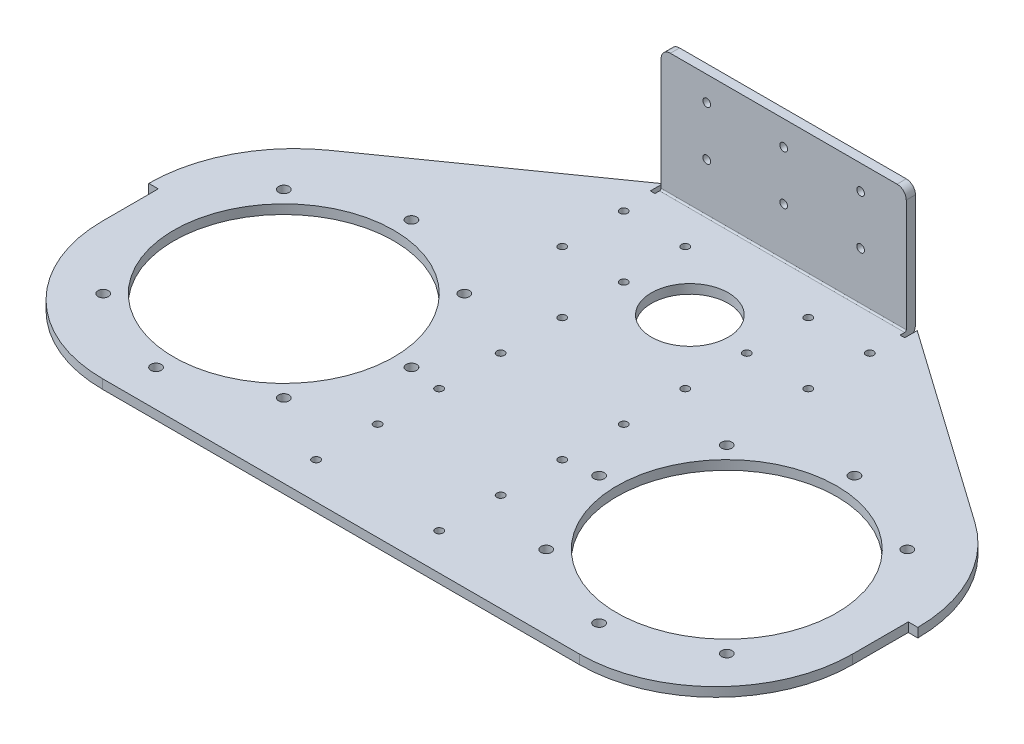
SolidWorks part; units mm, degrees
ref_plane "Спереди" through (0, 0, 0) normal (0, 0, 1) x (1, 0, 0)
ref_plane "Сверху" through (0, 0, 0) normal (0, 1, 0) x (1, 0, 0)
ref_plane "Справа" through (0, 0, 0) normal (1, 0, 0) x (0, 0, -1)
ref_plane "Плоскость4" through (0, 247, 0) normal (0, -1, 0) x (1, 0, 0)
sketch "Эскиз1" plane through (0, 247, 0) normal (0, -1, 0) x (1, 0, 0)
  line L0 (124.9999, -9.1) -> (-124.9999, -9.1)
  line L1 (-104.8475, -47.8377) -> (-41.3416, -92.5553)
  line L2 (-41.3416, -92.5553) -> (-41.3416, -88.5)
  line L3 (-41.3416, -88.5) -> (41.3416, -88.5)
  line L4 (41.3416, -88.5) -> (41.3416, -92.5553)
  line L5 (41.3416, -92.5553) -> (104.8475, -47.8377)
  arc A0 (-124.9999, -9.1) -> (-104.8475, -47.8377) centre (-77.5, -9) ccw
  arc A1 (104.8475, -47.8377) -> (124.9999, -9.1) centre (77.5, -9) ccw
extrude "Бобышка-Вытянуть1" add sketch "Эскиз1" against normal blind 3
sketch "Эскиз2" plane through (0, 0, -9.1) normal (0, 0, 1) x (1, 0, 0)
  line L0 (121.9, 247) -> (-121.9, 247)
  line L1 (-121.9, 247) -> (-121.9, 250)
  line L2 (-121.9, 250) -> (121.9, 250)
  line L3 (121.9, 250) -> (121.9, 247)
extrude "Бобышка-Вытянуть2" add sketch "Эскиз2" along normal blind 62.5
sketch "Эскиз3" plane through (0, 0, -88.5) normal (0, 0, -1) x (-1, 0, 0)
  line L0 (39.8416, 250) -> (39.8416, 247)
  line L1 (39.8416, 247) -> (-39.8416, 247)
  line L2 (-39.8416, 247) -> (-39.8416, 250)
  line L3 (-39.8416, 250) -> (39.8416, 250)
extrude "Бобышка-Вытянуть3" add sketch "Эскиз3" along normal blind 5
sketch "Эскиз4" plane through (0, 250, 0) normal (0, 1, 0) x (-1, 0, 0)
  line L0 (39.8416, -93.5) -> (-39.8416, -93.5)
  line L1 (-39.8416, -93.5) -> (-39.8416, -90.5)
  line L2 (-39.8416, -90.5) -> (39.8416, -90.5)
  line L3 (39.8416, -90.5) -> (39.8416, -93.5)
extrude "Бобышка-Вытянуть4" add sketch "Эскиз4" along normal blind 40
hole_wizard "Диаметр отверстия Ø2.5 (2.5)1" positions "Эскиз6" profile "Эскиз5" hole size "Ø2.5" standard "Ansi Metric"
sketch "Эскиз6" plane through (0, 0, -90.5) normal (0, 0, 1) x (1, 0, 0)
  point P0 (25, 266)
  point P1 (25, 282)
  point P2 (0, 266)
  point P3 (0, 282)
  point P4 (-25, 266)
  point P5 (-25, 282)
sketch "Эскиз5" plane through (25, 266, -90.5) normal (1, 0, 0) x (0, -1, 0)
  line L0 (0, 0) -> (0, 3)
  line L1 (0, 3) -> (1.25, 3)
  line L2 (1.25, 3) -> (1.25, 0)
  line L5 (1.25, 0) -> (0, 0)
  line L11 (0, -6.35) -> (0, 107.95) construction
  dimension "Диаметр сквозного отверстия" = 2.5
  dimension "Глубина сквозного отверстия" = 3
hole_wizard "Диаметр отверстия Ø25.0 (25)1" positions "Эскиз8" profile "Эскиз7" hole size "Ø25.0" standard "Ansi Metric"
sketch "Эскиз8" plane through (0, 247, 0) normal (0, -1, 0) x (-1, 0, 0)
  point P0 (0, 60)
sketch "Эскиз7" plane through (0, 247, -60) normal (1, 0, 0) x (0, 0, -1)
  line L0 (0, 0) -> (0, 43)
  line L1 (0, 43) -> (12.5, 43)
  line L2 (12.5, 43) -> (12.5, 0)
  line L5 (12.5, 0) -> (0, 0)
  line L11 (0, -6.35) -> (0, 107.95) construction
  dimension "Диаметр сквозного отверстия" = 25
  dimension "Глубина сквозного отверстия" = 43
hole_wizard "Отверстие с зазором M641" positions "Эскиз10" profile "Эскиз9" hole size "M64" standard "Ansi Metric"
sketch "Эскиз10" plane through (0, 247, 0) normal (0, -1, 0) x (-1, 0, 0)
  point P0 (72, 0)
  point P1 (-72, 0)
sketch "Эскиз9" plane through (-72, 247, 0) normal (1, 0, 0) x (0, 0, -1)
  line L0 (0, 0) -> (0, 43)
  line L1 (0, 43) -> (35.75, 43)
  line L2 (35.75, 43) -> (35.75, 0)
  line L5 (35.75, 0) -> (0, 0)
  line L11 (0, -6.35) -> (0, 107.95) construction
  dimension "Диаметр сквозного отверстия" = 71.5
  dimension "Глубина сквозного отверстия" = 43
hole_wizard "Диаметр отверстия Ø3.4 (3.4)1" positions "Эскиз12" profile "Эскиз11" hole size "Ø3.4" standard "Ansi Metric"
sketch "Эскиз12" plane through (0, 247, 0) normal (0, -1, 0) x (-1, 0, 0)
  point P0 (72, 41.5)
  point P1 (42.6551, 29.3449)
  point P2 (30.5, 0)
  point P3 (42.6551, -29.3449)
  point P4 (72, -41.5)
  point P5 (101.3449, -29.3449)
  point P6 (101.3449, 29.3449)
  point P7 (-101.3449, 29.3449)
  point P8 (-101.3449, -29.3449)
  point P9 (-72, -41.5)
  point P10 (-42.6551, -29.3449)
  point P11 (-30.5, 0)
  point P12 (-42.6551, 29.3449)
  point P13 (-72, 41.5)
sketch "Эскиз11" plane through (-72, 247, -41.5) normal (1, 0, 0) x (0, 0, -1)
  line L0 (0, 0) -> (0, 43)
  line L1 (0, 43) -> (1.7, 43)
  line L2 (1.7, 43) -> (1.7, 0)
  line L5 (1.7, 0) -> (0, 0)
  line L11 (0, -6.35) -> (0, 107.95) construction
  dimension "Диаметр сквозного отверстия" = 3.4
  dimension "Глубина сквозного отверстия" = 43
hole_wizard "Диаметр отверстия Ø2.5 (2.5)2" positions "Эскиз14" profile "Эскиз13" hole size "Ø2.5" standard "Ansi Metric"
sketch "Эскиз14" plane through (0, 247, 0) normal (0, -1, 0) x (-1, 0, 0)
  point P0 (-20, 58.5)
  point P1 (20, 18.5)
  point P2 (-20, 18.5)
  point P3 (-20, -1.5)
  point P4 (20, -21.5)
  point P5 (20, -41.5)
  point P6 (-20, -41.5)
  point P7 (-20, -21.5)
  point P8 (20, -1.5)
  point P9 (-20, 38.5)
  point P10 (20, 38.5)
  point P11 (-40, 58.5)
  point P12 (-40, 78.5)
  point P13 (-20, 78.5)
  point P14 (20, 58.5)
  point P15 (20, 78.5)
  point P16 (40, 58.5)
  point P17 (40, 78.5)
sketch "Эскиз13" plane through (20, 247, -58.5) normal (1, 0, 0) x (0, 0, -1)
  line L0 (0, 0) -> (0, 43)
  line L1 (0, 43) -> (1.25, 43)
  line L2 (1.25, 43) -> (1.25, 0)
  line L5 (1.25, 0) -> (0, 0)
  line L11 (0, -6.35) -> (0, 107.95) construction
  dimension "Диаметр сквозного отверстия" = 2.5
  dimension "Глубина сквозного отверстия" = 43
fillet "Скругление1" radius 0.5 1 edges at (0, 250, -90.5)
fillet "Скругление2" radius 3 2 edges at (-39.8416, 290, -92) (39.8416, 290, -92)
fillet "Скругление3" radius 3.5 1 edges at (0, 247, -93.5)
fillet "Скругление4" radius 44.4 2 edges at (121.9, 248.5, 53.4) (-121.9, 248.5, 53.4)
